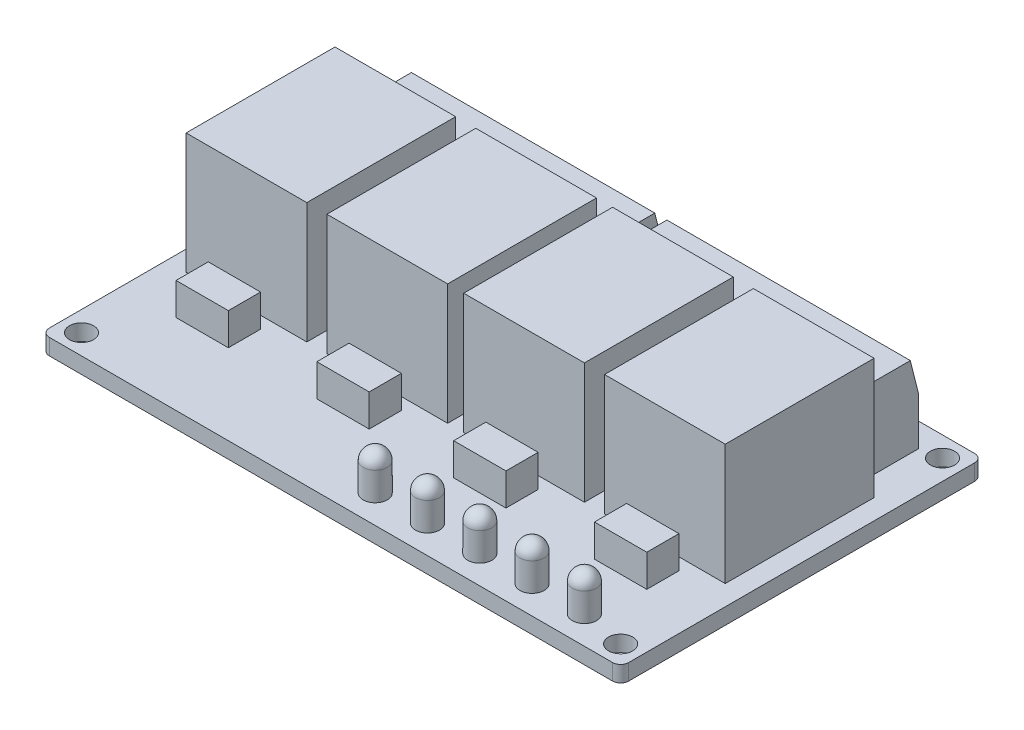
SolidWorks part; units mm, degrees
ref_plane "Front Plane" through (0, 0, 0) normal (0, 0, 1) x (1, 0, 0)
ref_plane "Top Plane" through (0, 0, 0) normal (0, 1, 0) x (1, 0, 0)
ref_plane "Right Plane" through (0, 0, 0) normal (1, 0, 0) x (0, 0, -1)
sketch "Sketch1" plane through (0, 0, 0) normal (0, 1, 0) x (1, 0, 0)
  line L0 (-33.5, 21.5) -> (-33.5, 22.5) construction
  line L1 (-35, -22.5) -> (35, -22.5)
  line L2 (-36, -21.5) -> (-36, 21.5)
  line L3 (-35, 22.5) -> (35, 22.5)
  line L4 (36, -21.5) -> (36, 21.5)
  line L5 (-36, -22.5) -> (36, 22.5) construction
  line L6 (-36, 22.5) -> (36, -22.5) construction
  line L7 (-35, 20) -> (-36, 20) construction
  line L8 (0, 0) -> (0, 22.5) construction
  line L9 (0, 0) -> (36, 0) construction
  circle A0 centre (-33.5, 20) radius 1.5
  circle A1 centre (33.5, 20) radius 1.5
  circle A2 centre (33.5, -20) radius 1.5
  circle A3 centre (-33.5, -20) radius 1.5
  arc A4 (35, 22.5) -> (36, 21.5) centre (35, 21.5) cw
  arc A5 (35, -22.5) -> (36, -21.5) centre (35, -21.5) ccw
  arc A6 (-35, -22.5) -> (-36, -21.5) centre (-35, -21.5) cw
  arc A7 (-36, 21.5) -> (-35, 22.5) centre (-35, 21.5) cw
  point P0 (0, 0)
  dimension "D3" = 3
  dimension "D5" = 1
  dimension "D1" = 72
  dimension "D2" = 45
  dimension "D4" = 1
extrude "Boss-Extrude1" add sketch "Sketch1" along normal blind 2
sketch "Sketch2" plane through (0, 2, 0) normal (0, 1, 0) x (1, 0, 0)
  line L0 (0, 0) -> (0, 22.5) construction
  line L1 (-31, 19.5) -> (-0.75, 19.5)
  line L2 (-31, 19.5) -> (-31, 12.5)
  line L3 (-31, 12.5) -> (-0.75, 12.5)
  line L4 (31, 19.5) -> (31, 12.5)
  line L5 (35, 22.5) -> (-35, 22.5) construction
  line L6 (-31, 19.5) -> (-36, 19.5) construction
  line L7 (-36, 21.5) -> (-36, -21.5) construction
  line L8 (31, 19.5) -> (36, 19.5) construction
  line L9 (36, -21.5) -> (36, 21.5) construction
  line L10 (-0.75, 19.5) -> (-0.75, 12.5)
  line L11 (0.75, 12.5) -> (0.75, 19.5)
  line L12 (0.75, 19.5) -> (31, 19.5)
  line L13 (0.75, 12.5) -> (31, 12.5)
  line L14 (-0.75, 19.5) -> (0, 19.5) construction
  line L15 (0, 19.5) -> (0.75, 19.5) construction
  dimension "D1" = 3
  dimension "D2" = 62
  dimension "D3" = 7
  dimension "D4" = 1.5
extrude "Boss-Extrude2" add sketch "Sketch2" along normal blind 10
sketch "Sketch3" plane through (-31, 0, 0) normal (-1, 0, 0) x (0, 0, 1)
  line L0 (-19.5, 8) -> (-18.5, 12)
  line L1 (-19.5, 12) -> (-19.5, 2) construction
  line L2 (-19.5, 12) -> (-12.5, 12) construction
  line L3 (-18.5, 12) -> (-19.5, 12)
  line L4 (-19.5, 12) -> (-19.5, 8)
  line L5 (-12.5, 8) -> (-14, 12)
  line L6 (-12.5, 12) -> (-12.5, 2) construction
  line L7 (-14, 12) -> (-12.5, 12)
  line L8 (-12.5, 12) -> (-12.5, 8)
  dimension "D1" = 1
  dimension "D2" = 1.5
  dimension "D3" = 6
extrude "Cut-Extrude1" cut sketch "Sketch3" against normal through all
sketch "Sketch4" plane through (0, 2, 0) normal (0, 1, 0) x (1, 0, 0)
  line L0 (-36, 11.5) -> (-33.5, 11.5) construction
  line L1 (33.5, 11.5) -> (18.5, 11.5)
  line L2 (33.5, 11.5) -> (33.5, -7)
  line L3 (33.5, -7) -> (18.5, -7)
  line L4 (18.5, 11.5) -> (18.5, -7)
  line L5 (16, 11.5) -> (1, 11.5)
  line L6 (16, 11.5) -> (16, -7)
  line L7 (16, -7) -> (1, -7)
  line L8 (1, 11.5) -> (1, -7)
  line L9 (-1, -7) -> (-16, -7)
  line L10 (-1, -7) -> (-1, 11.5)
  line L11 (-1, 11.5) -> (-16, 11.5)
  line L12 (-16, -7) -> (-16, 11.5)
  line L13 (-18.5, 11.5) -> (-33.5, 11.5)
  line L14 (-18.5, 11.5) -> (-18.5, -7)
  line L15 (-18.5, -7) -> (-33.5, -7)
  line L16 (-33.5, 11.5) -> (-33.5, -7)
  line L17 (-36, 21.5) -> (-36, -21.5) construction
  line L18 (-18.5, 11.5) -> (-16, 11.5) construction
  line L19 (-1, 11.5) -> (1, 11.5) construction
  line L20 (16, 11.5) -> (18.5, 11.5) construction
  line L21 (33.5, 11.5) -> (36, 11.5) construction
  line L22 (36, -21.5) -> (36, 21.5) construction
  line L23 (-31, 12.5) -> (-0.75, 12.5) construction
  dimension "D1" = 15
  dimension "D2" = 18.5
  dimension "D3" = 2.5
  dimension "D4" = 1
extrude "Boss-Extrude3" add sketch "Sketch4" along normal blind 15
sketch "Sketch5" plane through (0, 2, 0) normal (0, 1, 0) x (1, 0, 0)
  line L0 (-26, -8.5) -> (-26, -7) construction
  line L1 (-22.75, -12.5) -> (-29.25, -12.5)
  line L2 (-22.75, -12.5) -> (-22.75, -8.5)
  line L3 (-22.75, -8.5) -> (-29.25, -8.5)
  line L4 (-29.25, -12.5) -> (-29.25, -8.5)
  line L5 (-11.75, -12.5) -> (-5.25, -12.5)
  line L6 (-11.75, -12.5) -> (-11.75, -8.5)
  line L7 (-11.75, -8.5) -> (-5.25, -8.5)
  line L8 (-5.25, -12.5) -> (-5.25, -8.5)
  line L9 (5.25, -8.5) -> (11.75, -8.5)
  line L10 (5.25, -8.5) -> (5.25, -12.5)
  line L11 (5.25, -12.5) -> (11.75, -12.5)
  line L12 (11.75, -8.5) -> (11.75, -12.5)
  line L13 (22.75, -8.5) -> (29.25, -8.5)
  line L14 (22.75, -8.5) -> (22.75, -12.5)
  line L15 (22.75, -12.5) -> (29.25, -12.5)
  line L16 (29.25, -8.5) -> (29.25, -12.5)
  line L17 (-33.5, -7) -> (-18.5, -7) construction
  line L18 (-8.5, -7) -> (-8.5, -8.5) construction
  line L19 (-16, -7) -> (-1, -7) construction
  line L20 (8.5, -7) -> (8.5, -8.5) construction
  line L21 (1, -7) -> (16, -7) construction
  line L22 (26, -7) -> (26, -8.5) construction
  line L23 (18.5, -7) -> (33.5, -7) construction
  dimension "D1" = 4
  dimension "D2" = 6.5
  dimension "D3" = 1.5
extrude "Boss-Extrude4" add sketch "Sketch5" along normal blind 4
sketch "Sketch6" plane through (0, 2, 0) normal (0, 1, 0) x (1, 0, 0)
  line L0 (29.5, -19) -> (36, -19) construction
  line L1 (36, -21.5) -> (36, 21.5) construction
  line L2 (28, -20.5) -> (28, -22.5) construction
  line L3 (-35, -22.5) -> (35, -22.5) construction
  circle A0 centre (28, -19) radius 1.5
  circle A1 centre (21.5, -19) radius 1.5
  circle A2 centre (15, -19) radius 1.5
  circle A3 centre (8.5, -19) radius 1.5
  circle A4 centre (2, -19) radius 1.5
  dimension "D1" = 3
  dimension "D2" = 6.5
  dimension "D3" = 2
  dimension "D4" = 5
extrude "Boss-Extrude5" add sketch "Sketch6" along normal blind 5
fillet "Fillet1" radius 1.5 1 edges at (2, 7, 20.5)
fillet "Fillet2" radius 1.5 1 edges at (8.5, 7, 20.5)
fillet "Fillet3" radius 1.5 1 edges at (15, 7, 20.5)
fillet "Fillet4" radius 1.5 1 edges at (21.5, 7, 20.5)
fillet "Fillet5" radius 1.5 1 edges at (28, 7, 20.5)
